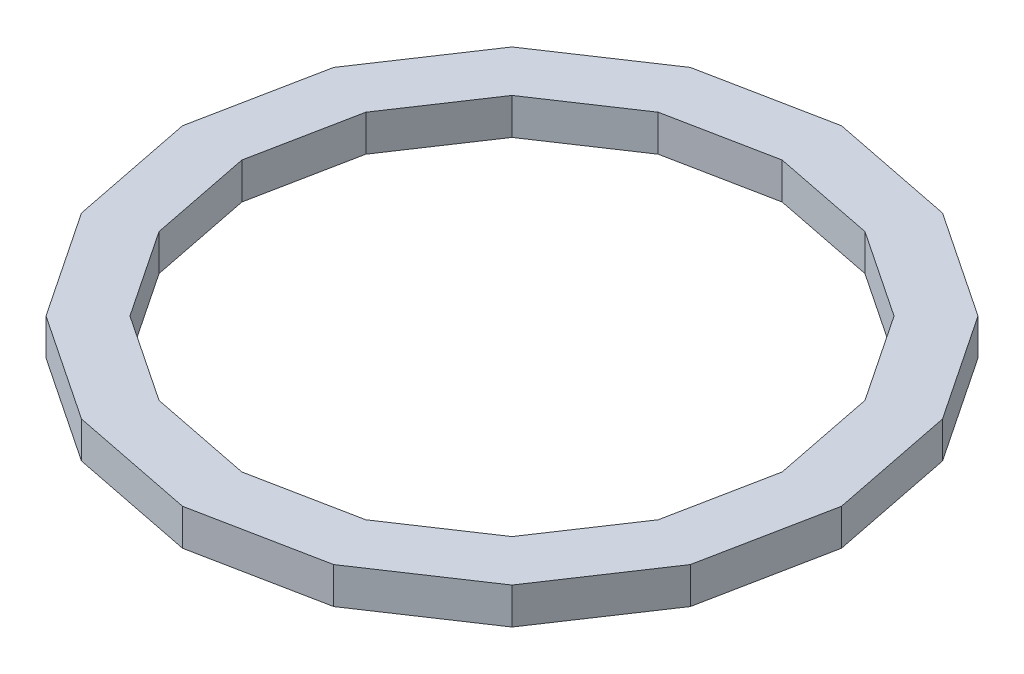
SolidWorks part; units mm, degrees
ref_plane "Front Plane" through (0, 0, 0) normal (0, 0, 1) x (1, 0, 0)
ref_plane "Top Plane" through (0, 0, 0) normal (0, 1, 0) x (1, 0, 0)
ref_plane "Right Plane" through (0, 0, 0) normal (1, 0, 0) x (0, 0, -1)
sketch "Sketch1" plane through (0, 0, 0) normal (0, 1, 0) x (1, 0, 0)
  line L1 (141.4327, 0) -> (130.6668, 54.124)
  line L2 (130.6668, 54.124) -> (100.008, 100.008)
  line L3 (100.008, 100.008) -> (54.124, 130.6668)
  line L4 (54.124, 130.6668) -> (0, 141.4327)
  line L5 (0, 141.4327) -> (-54.124, 130.6668)
  line L6 (-54.124, 130.6668) -> (-100.008, 100.008)
  line L7 (-100.008, 100.008) -> (-130.6668, 54.124)
  line L8 (-130.6668, 54.124) -> (-141.4327, 0)
  line L9 (-141.4327, 0) -> (-130.6668, -54.124)
  line L10 (-130.6668, -54.124) -> (-100.008, -100.008)
  line L11 (-100.008, -100.008) -> (-54.124, -130.6668)
  line L12 (-54.124, -130.6668) -> (0, -141.4327)
  line L13 (0, -141.4327) -> (54.124, -130.6668)
  line L14 (54.124, -130.6668) -> (100.008, -100.008)
  line L15 (100.008, -100.008) -> (130.6668, -54.124)
  line L16 (130.6668, -54.124) -> (141.4327, 0)
  line L17 (172.5098, 0) -> (159.3783, 66.0167)
  line L18 (159.3783, 66.0167) -> (121.9829, 121.9829)
  line L19 (121.9829, 121.9829) -> (66.0167, 159.3783)
  line L20 (66.0167, 159.3783) -> (0, 172.5098)
  line L21 (0, 172.5098) -> (-66.0167, 159.3783)
  line L22 (-66.0167, 159.3783) -> (-121.9829, 121.9829)
  line L23 (-121.9829, 121.9829) -> (-159.3783, 66.0167)
  line L24 (-159.3783, 66.0167) -> (-172.5098, 0)
  line L25 (-172.5098, 0) -> (-159.3783, -66.0167)
  line L26 (-159.3783, -66.0167) -> (-121.9829, -121.9829)
  line L27 (-121.9829, -121.9829) -> (-66.0167, -159.3783)
  line L28 (-66.0167, -159.3783) -> (0, -172.5098)
  line L29 (0, -172.5098) -> (66.0167, -159.3783)
  line L30 (66.0167, -159.3783) -> (121.9829, -121.9829)
  line L31 (121.9829, -121.9829) -> (159.3783, -66.0167)
  line L32 (159.3783, -66.0167) -> (172.5098, 0)
  circle A1 centre (0, 0) radius 138.7151 construction
  circle A2 centre (0, 0) radius 169.1951 construction
  dimension "D1" = 30.48
  dimension "D2" = 67.31
extrude "Boss-Extrude1" add sketch "Sketch1" along normal blind 19.05
